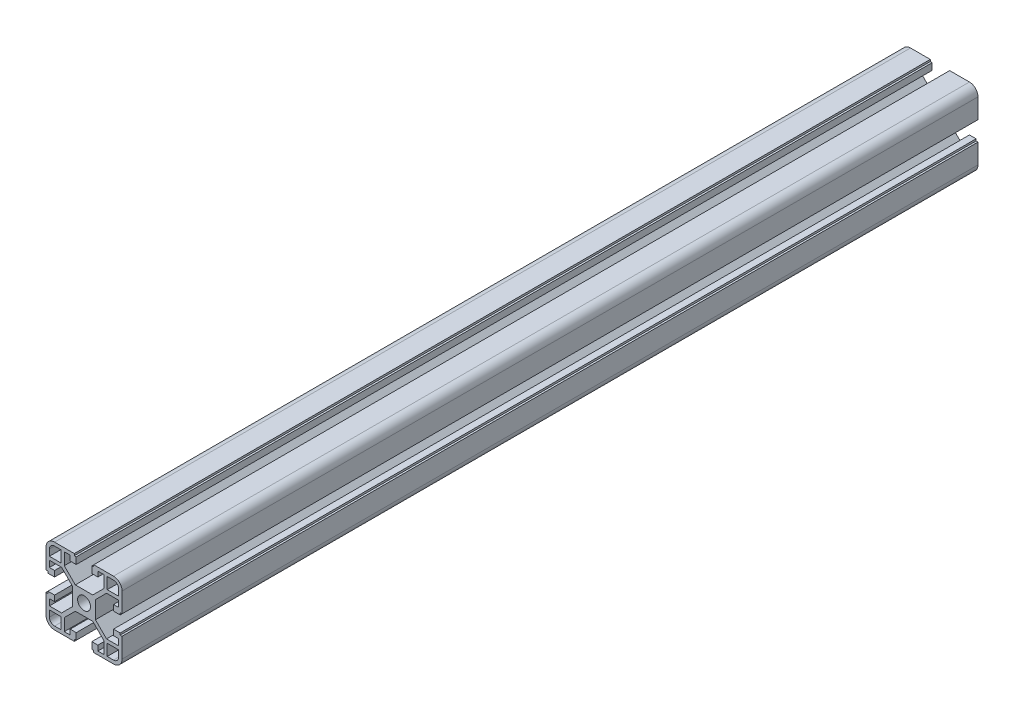
SolidWorks part; units mm, degrees
material "6063-T5"
ref_plane "Front Plane" through (0, 0, 0) normal (0, 0, 1) x (1, 0, 0)
ref_plane "Top Plane" through (0, 0, 0) normal (0, 1, 0) x (1, 0, 0)
ref_plane "Right Plane" through (0, 0, 0) normal (1, 0, 0) x (0, 0, -1)
sketch "Sketch3" plane through (0, 0, 0) normal (0, 0, 1) x (1, 0, 0)
  line L0 (17.9333, 92.7) -> (169.2667, 92.7) construction
  line L1 (-6, 6) -> (6, 6)
  line L2 (-6, 6) -> (-6, -6)
  line L3 (-6, -6) -> (6, -6)
  line L4 (6, 6) -> (6, -6)
  line L5 (0, 0) -> (20.1249, 20.1249) construction
  line L6 (4.5736, 4.5736) -> (11.4537, 11.4537) construction
  line L7 (5.2807, 3.8665) -> (12.0153, 10.6011)
  line L8 (3.8665, 5.2807) -> (10.7858, 12.2)
  line L13 (11.8142, 10.4) -> (18.2, 10.4)
  line L14 (6, 0) -> (23.1042, 0) construction
  line L15 (0, 6) -> (0, 13.9346) construction
  line L16 (4.5736, 4.5736) -> (11.8129, 11.8129) construction
  line L17 (5.2807, 3.8665) -> (12.52, 11.1058) construction
  line L18 (3.8665, 5.2807) -> (11.1058, 12.52) construction
  line L19 (10.4, 11.8142) -> (10.4, 18.2)
  line L20 (10.4, 18.2) -> (7.2581, 18.2)
  line L21 (-20, 20) -> (20, 20) construction
  line L22 (-20, 20) -> (-20, -20) construction
  line L23 (-20, -20) -> (20, -20) construction
  line L24 (20, 20) -> (20, -20) construction
  line L25 (7.2581, 18.2) -> (7.2581, 15.5)
  line L26 (7.2581, 15.5) -> (4.1, 15.5)
  line L27 (4.1, 15.5) -> (4.1, 19)
  line L28 (4.1, 19) -> (5.1, 19)
  line L29 (5.1, 19) -> (5.1, 20)
  line L30 (5.1, 20) -> (15.5, 20)
  line L31 (20, 15.5) -> (20, 5.1)
  line L32 (20, 5.1) -> (19, 5.1)
  line L33 (19, 5.1) -> (19, 4.1)
  line L34 (19, 4.1) -> (15.5, 4.1)
  line L35 (15.5, 4.1) -> (15.5, 7.1)
  line L36 (15.5, 7.1) -> (18.2, 7.1)
  line L37 (18.2, 7.1) -> (18.2, 10.4)
  line L42 (18.2, 12.2) -> (12.2, 12.2)
  line L43 (12.2, 18.2) -> (12.2, 18.2)
  line L44 (12.2, 18.2) -> (12.2, 18.2)
  line L45 (12.2, 18.2) -> (12.2, 18.2)
  line L46 (12.2, 18.2) -> (12.2, 18.2)
  line L47 (12.2, 18.2) -> (12.2, 18.2)
  line L48 (12.2, 18.2) -> (12.2, 18.2)
  line L49 (12.2, 18.2) -> (15.5, 18.2)
  line L50 (18.2, 15.5) -> (18.2, 12.2)
  line L51 (18.2, 12.2) -> (18.2, 12.2)
  line L52 (18.2, 12.2) -> (18.2, 12.2)
  line L53 (18.2, 12.2) -> (18.2, 12.2)
  line L54 (18.2, 12.2) -> (18.2, 12.2)
  line L55 (18.2, 12.2) -> (18.2, 12.2)
  line L56 (18.2, 12.2) -> (18.2, 12.2)
  line L57 (12.2, 12.2) -> (12.2, 18.2)
  line L58 (11.8142, 12.2) -> (18.2, 12.2) construction
  line L59 (12.2, 11.8142) -> (12.2, 18.2) construction
  line L60 (-18.2, 15.5) -> (-18.2, 12.2)
  line L61 (-12.2, 18.2) -> (-15.5, 18.2)
  line L62 (-12.2, 12.2) -> (-12.2, 18.2)
  line L63 (-18.2, 12.2) -> (-12.2, 12.2)
  line L64 (-11.8142, 10.4) -> (-18.2, 10.4)
  line L65 (-18.2, 7.1) -> (-18.2, 10.4)
  line L66 (-15.5, 7.1) -> (-18.2, 7.1)
  line L67 (-15.5, 4.1) -> (-15.5, 7.1)
  line L68 (-19, 4.1) -> (-15.5, 4.1)
  line L69 (-19, 5.1) -> (-19, 4.1)
  line L70 (-20, 5.1) -> (-19, 5.1)
  line L71 (-20, 15.5) -> (-20, 5.1)
  line L72 (-5.1, 20) -> (-15.5, 20)
  line L73 (-5.1, 19) -> (-5.1, 20)
  line L74 (-4.1, 19) -> (-5.1, 19)
  line L75 (-4.1, 15.5) -> (-4.1, 19)
  line L76 (-7.2581, 15.5) -> (-4.1, 15.5)
  line L77 (-7.2581, 18.2) -> (-7.2581, 15.5)
  line L78 (-10.4, 18.2) -> (-7.2581, 18.2)
  line L79 (-10.4, 11.8142) -> (-10.4, 18.2)
  line L80 (-10.4, 11.8142) -> (-4.5858, 6)
  line L81 (-11.8142, 10.4) -> (-6, 4.5858)
  line L82 (-18.2, -15.5) -> (-18.2, -12.2)
  line L83 (-18.2, -12.2) -> (-12.2, -12.2)
  line L84 (-12.2, -12.2) -> (-12.2, -18.2)
  line L85 (-12.2, -18.2) -> (-15.5, -18.2)
  line L86 (-20, -15.5) -> (-20, -5.1)
  line L87 (-20, -5.1) -> (-19, -5.1)
  line L88 (-19, -5.1) -> (-19, -4.1)
  line L89 (-19, -4.1) -> (-15.5, -4.1)
  line L90 (-15.5, -4.1) -> (-15.5, -7.1)
  line L91 (-15.5, -7.1) -> (-18.2, -7.1)
  line L92 (-18.2, -7.1) -> (-18.2, -10.4)
  line L93 (-11.8142, -10.4) -> (-18.2, -10.4)
  line L94 (-11.8142, -10.4) -> (-6, -4.5858)
  line L95 (-10.4, -11.8142) -> (-4.5858, -6)
  line L96 (-10.4, -11.8142) -> (-10.4, -18.2)
  line L97 (-10.4, -18.2) -> (-7.2581, -18.2)
  line L98 (-7.2581, -18.2) -> (-7.2581, -15.5)
  line L99 (-7.2581, -15.5) -> (-4.1, -15.5)
  line L100 (-4.1, -15.5) -> (-4.1, -19)
  line L101 (-4.1, -19) -> (-5.1, -19)
  line L102 (-5.1, -19) -> (-5.1, -20)
  line L103 (-5.1, -20) -> (-15.5, -20)
  line L104 (12.2, -18.2) -> (15.5, -18.2)
  line L105 (12.2, -12.2) -> (12.2, -18.2)
  line L106 (18.2, -12.2) -> (12.2, -12.2)
  line L107 (18.2, -15.5) -> (18.2, -12.2)
  line L108 (5.1, -20) -> (15.5, -20)
  line L109 (5.1, -19) -> (5.1, -20)
  line L110 (4.1, -19) -> (5.1, -19)
  line L111 (4.1, -15.5) -> (4.1, -19)
  line L112 (7.2581, -15.5) -> (4.1, -15.5)
  line L113 (10.4, -18.2) -> (7.2581, -18.2)
  line L114 (7.2581, -18.2) -> (7.2581, -15.5)
  line L115 (10.4, -11.8142) -> (10.4, -18.2)
  line L116 (10.4, -11.8142) -> (4.5858, -6)
  line L117 (11.8142, -10.4) -> (6, -4.5858)
  line L118 (11.8142, -10.4) -> (18.2, -10.4)
  line L119 (18.2, -7.1) -> (18.2, -10.4)
  line L120 (20, -15.5) -> (20, -5.1)
  line L121 (20, -5.1) -> (19, -5.1)
  line L122 (19, -5.1) -> (19, -4.1)
  line L123 (15.5, -7.1) -> (18.2, -7.1)
  line L124 (15.5, -4.1) -> (15.5, -7.1)
  line L125 (19, -4.1) -> (15.5, -4.1)
  circle A0 centre (0, 0) radius 3.4
  arc A1 (15.5, 20) -> (20, 15.5) centre (15.5, 15.5) cw
  arc A2 (15.5, 18.2) -> (18.2, 15.5) centre (15.5, 15.5) cw
  arc A3 (-15.5, 18.2) -> (-18.2, 15.5) centre (-15.5, 15.5) ccw
  arc A4 (-15.5, 20) -> (-20, 15.5) centre (-15.5, 15.5) ccw
  arc A5 (-15.5, -18.2) -> (-18.2, -15.5) centre (-15.5, -15.5) cw
  arc A6 (-15.5, -20) -> (-20, -15.5) centre (-15.5, -15.5) cw
  arc A7 (15.5, -18.2) -> (18.2, -15.5) centre (15.5, -15.5) ccw
  arc A8 (15.5, -20) -> (20, -15.5) centre (15.5, -15.5) ccw
  point P7 (6, 0)
  point P8 (0, 6)
  point P36 (0, 20)
  point P37 (-20, 0)
  dimension "D3" = 6.8
  dimension "D28" = 4.5
  dimension "D1" = 12
  dimension "D2" = 12
  dimension "D6" = 10.4
  dimension "D7" = 10.4
  dimension "D8" = 40
  dimension "D9" = 40
  dimension "D10" = 1
  dimension "D11" = 1
  dimension "D12" = 1.8
  dimension "D13" = 1.8
  dimension "D14" = 2
  dimension "D17" = 1.8
  dimension "D18" = 1.8
  dimension "D19" = 1
  dimension "D20" = 1
  dimension "D21" = 3.5
  dimension "D22" = 5.1
  dimension "D23" = 4.1
  dimension "D24" = 3
  dimension "D25" = 3.5
  dimension "D26" = 4.1
  dimension "D27" = 5.1
  dimension "D4" = 1
  dimension "D5" = 1
  dimension "D29" = 1.8
extrude "Boss-Extrude1" add sketch "Sketch3" along normal blind 450
